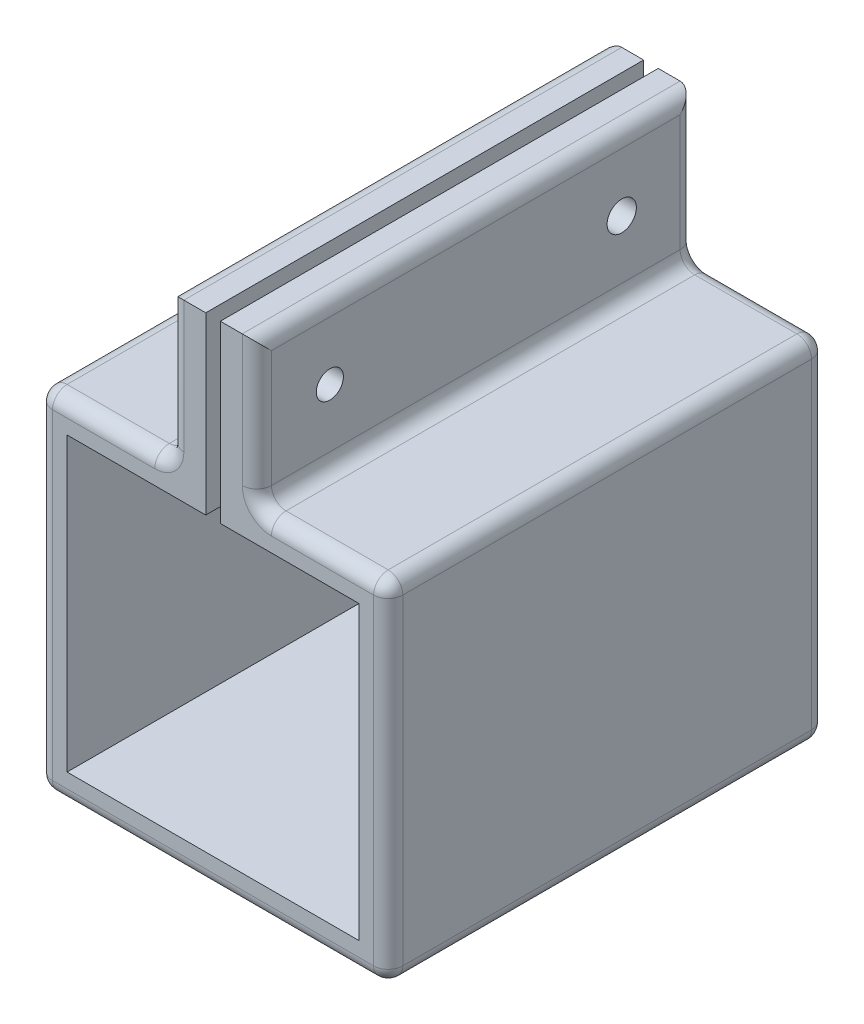
SolidWorks part; units mm, degrees
ref_plane "前视基准面" through (0, 0, 0) normal (0, 0, 1) x (1, 0, 0)
ref_plane "上视基准面" through (0, 0, 0) normal (0, 1, 0) x (1, 0, 0)
ref_plane "右视基准面" through (0, 0, 0) normal (1, 0, 0) x (0, 0, -1)
sketch "草图1" plane through (0, 0, 0) normal (0, 0, 1) x (1, 0, 0)
  line L1 (-10, 10) -> (10, 10)
  line L2 (-10, 10) -> (-10, -10)
  line L3 (-10, -10) -> (10, -10)
  line L4 (10, 10) -> (10, -10)
  line L5 (-10, 10) -> (10, -10) construction
  line L6 (-10, -10) -> (10, 10) construction
  line L7 (-12, 12) -> (12, 12)
  line L8 (-12, 12) -> (-12, -12)
  line L9 (-12, -12) -> (12, -12)
  line L10 (12, 12) -> (12, -12)
  line L11 (-12, 12) -> (12, -12) construction
  line L12 (-12, -12) -> (12, 12) construction
  line L13 (-3, 22) -> (3, 22)
  line L14 (-3, 22) -> (-3, 10)
  line L15 (-3, 10) -> (3, 10)
  line L16 (3, 22) -> (3, 10)
  line L17 (-3, 22) -> (3, 10) construction
  line L18 (-3, 10) -> (3, 22) construction
  point P0 (0, 0)
  point P6 (0, 0)
  point P11 (0, 16)
  dimension "D1" = 20
  dimension "D2" = 20
  dimension "D3" = 24
  dimension "D4" = 24
  dimension "D5" = 12
  dimension "D6" = 6
  dimension "D7" = 0
extrude "凸台-拉伸1" add sketch "草图1" along normal blind 30 contours L16 L7 L14 L1 | L7 L16 L1 L4 L3 L2 L14 L8 L9 L10 | L16 L13 L14 L7
sketch "草图2" plane through (0, 0, 30) normal (0, 0, 1) x (1, 0, 0)
  line L1 (-0.5, 27.2832) -> (0.5, 27.2832)
  line L2 (-0.5, 27.2832) -> (-0.5, 9.4797)
  line L3 (-0.5, 9.4797) -> (0.5, 9.4797)
  line L4 (0.5, 27.2832) -> (0.5, 9.4797)
  line L5 (-0.5, 27.2832) -> (0.5, 9.4797) construction
  line L6 (-0.5, 9.4797) -> (0.5, 27.2832) construction
  point P0 (0, 18.3814)
  dimension "D1" = 1
  dimension "D2" = 0
extrude "切除-拉伸1" cut sketch "草图2" against normal blind 30
sketch "草图3" plane through (-3, 0, 0) normal (-1, 0, 0) x (0, 0, 1)
  line L0 (30, 22) -> (0, 22) construction
  line L1 (0, 22) -> (0, 12) construction
  line L2 (30, 22) -> (30, 12) construction
  circle A0 centre (5, 17) radius 1.0033
  circle A1 centre (25, 17) radius 0.9308
  dimension "D1" = 5
  dimension "D2" = 5
  dimension "D3" = 5
  dimension "D4" = 5
extrude "切除-拉伸2" cut sketch "草图3" against normal blind 30
fillet "圆角1" radius 1 22 edges at (-3, 22, 15) (3, 22, 15) (12, -12, 15) (12, 12, 15) (-12, 12, 15) (-12, -12, 15) (-3, 17, 0) (-3, 17, 30) (3, 17, 0) (3, 17, 30) (0, -12, 0) (0, -12, 30) (-3, 12, 15) (-7.5, 12, 0) (-7.5, 12, 30) (7.5, 12, 0) (7.5, 12, 30) (3, 12, 15) (12, 0, 0) (12, 0, 30) (-12, 0, 0) (-12, 0, 30)
